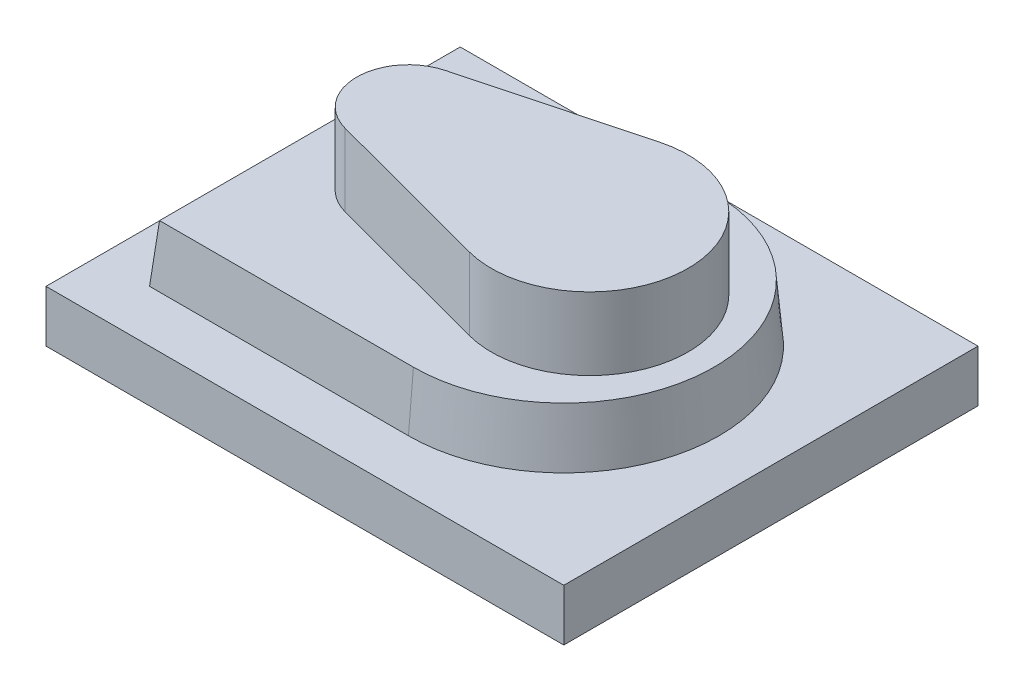
SolidWorks part; units mm, degrees
ref_plane "정면" through (0, 0, 0) normal (0, 0, 1) x (1, 0, 0)
ref_plane "윗면" through (0, 0, 0) normal (0, 1, 0) x (1, 0, 0)
ref_plane "우측면" through (0, 0, 0) normal (1, 0, 0) x (0, 0, -1)
sketch "스케치1" plane through (0, 0, 0) normal (0, 1, 0) x (1, 0, 0)
  line L1 (-50, 40) -> (50, 40)
  line L2 (-50, 40) -> (-50, -40)
  line L3 (-50, -40) -> (50, -40)
  line L4 (50, 40) -> (50, -40)
  line L5 (-50, 40) -> (50, -40) construction
  line L6 (-50, -40) -> (50, 40) construction
  point P0 (0, 0)
  dimension "D1" = 100
  dimension "D2" = 80
extrude "보스-돌출1" add sketch "스케치1" along normal blind 10
sketch "스케치2" plane through (0, 10, 0) normal (0, 1, 0) x (1, 0, 0)
  line L0 (10, 30) -> (-40, 30)
  line L1 (-40, 30) -> (-40, -30)
  line L2 (-40, -30) -> (10, -30)
  arc A0 (10, -30) -> (10, 30) centre (10, 0) ccw
  dimension "D1" = 60
  dimension "D2" = 10
  dimension "D3" = 10
  dimension "D4" = 60
extrude "보스-돌출2" add sketch "스케치2" along normal blind 11 draft 5
sketch "스케치3" plane through (0, 21, 0) normal (0, 1, 0) x (1, 0, 0)
  line L0 (-22.5714, 9.6637) -> (10.1143, 18.3611)
  line L1 (-22.5714, -9.6637) -> (10.1143, -18.3611)
  arc A0 (-22.5714, 9.6637) -> (-22.5714, -9.6637) centre (-20, 0) ccw
  arc A1 (10.1143, -18.3611) -> (10.1143, 18.3611) centre (15, 0) ccw
  point P1 (0, 0)
  point P8 (-24.0436, 4.2061)
  point P9 (0, 0)
  point P11 (0, 0)
  point P13 (0, 0)
  point P14 (12.5757, 18.8447)
  point P15 (10.1143, -18.3611)
  point P16 (0, 0)
  point P17 (-22.5714, -9.6637)
  dimension "D1" = 20
  dimension "D2" = 38
  dimension "D3" = 30
  dimension "D4" = 35
extrude "보스-돌출3" add sketch "스케치3" along normal blind 14
ref_plane "평면1" through (0, 0, 0) normal (0, 0, 1) x (1, 0, 0)
sketch "스케치4" plane through (0, 0, 0) normal (0, 0, 1) x (1, 0, 0)
  line L1 (-22.5714, 35) -> (10.1143, 35) construction
  arc A0 (-21.0782, 44.699) -> (34, 35) centre (9.5, 57.1077) ccw
  point P3 (29.6839, 31)
  point P4 (-15, 35)
  point P5 (27.1369, 44.1532)
  point P6 (0, 0)
  point P7 (-21.0782, 44.699)
  point P8 (34, 35)
  point P12 (34, 35)
  point P13 (34, 35)
  dimension "D1" = 33
  dimension "D3" = 35
  dimension "D2" = 4
ref_plane "평면2" through (34, 35, 0) normal (0.6699, 0.7424, 0) x (0.7424, -0.6699, 0)
sketch "스케치5" plane through (34, 35, 0) normal (0.6699, 0.7424, 0) x (0.7424, -0.6699, 0)
  line L0 (-47.389, 0) -> (0, 0) construction
  arc A0 (12.7895, -40.3356) -> (12.7895, 40.3356) centre (70, 0) cw
  point P5 (12.0709, -50.3401)
  point P6 (0, 0)
  point P7 (0, 0)
  dimension "D1" = 70
